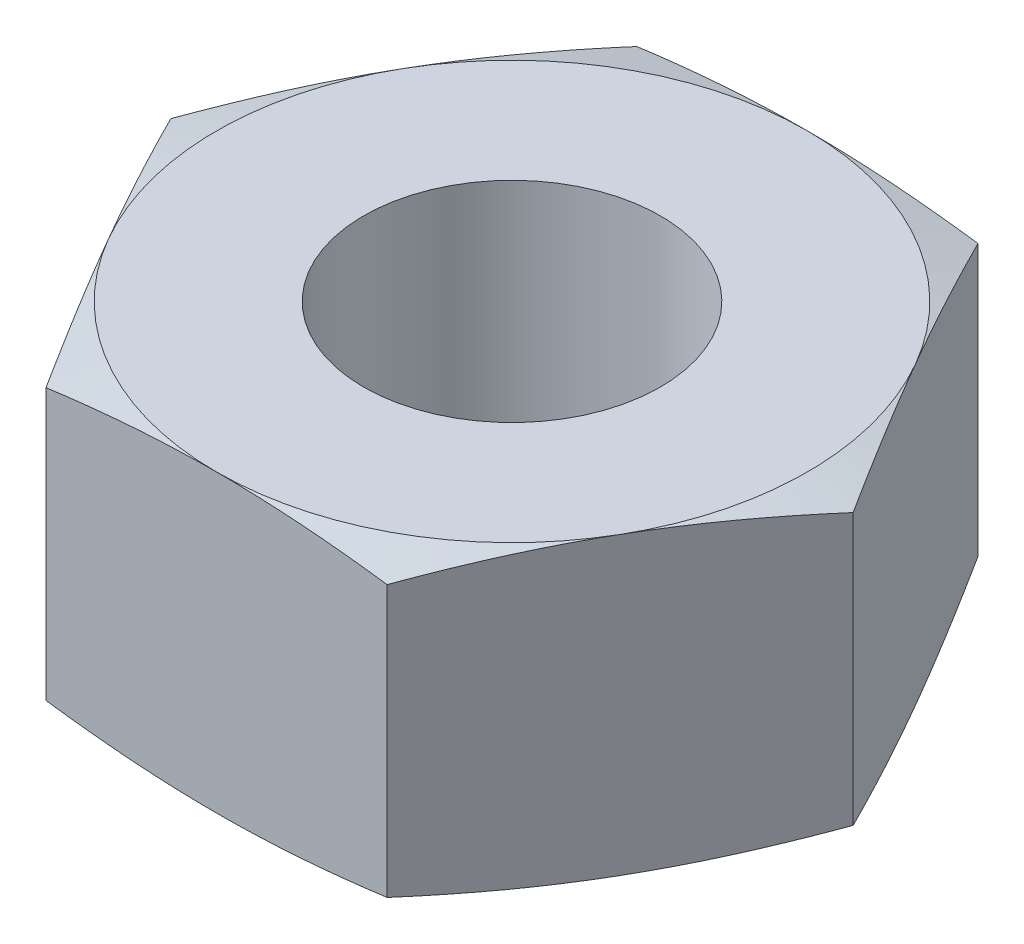
SolidWorks part; units mm, degrees
material "Plain Carbon Steel"
ref_plane "Front Plane" through (0, 0, 0) normal (0, 0, 1) x (1, 0, 0)
ref_plane "Top Plane" through (0, 0, 0) normal (0, 1, 0) x (1, 0, 0)
ref_plane "Right Plane" through (0, 0, 0) normal (1, 0, 0) x (0, 0, -1)
sketch "Sketch1" plane through (0, 0, 0) normal (0, 1, 0) x (1, 0, 0)
  line L1 (4.6188, 0) -> (2.3094, 4)
  line L2 (2.3094, 4) -> (-2.3094, 4)
  line L3 (-2.3094, 4) -> (-4.6188, 0)
  line L4 (-4.6188, 0) -> (-2.3094, -4)
  line L5 (-2.3094, -4) -> (2.3094, -4)
  line L6 (2.3094, -4) -> (4.6188, 0)
  circle A0 centre (0, 0) radius 4 construction
  dimension "D1" = 8
extrude "Extrude1" add sketch "Sketch1" along normal mid plane 4
sketch "Sketch2" plane through (0, 0, 0) normal (1, 0, 0) x (0, 0, -1)
  line L0 (-4, 2) -> (-78.064, -17.8454)
  line L1 (-78.064, -17.8454) -> (-78.064, 2)
  line L2 (-78.064, 2) -> (-4, 2)
  line L3 (0, 0) -> (0, 7.9376) construction
  dimension "D1" = 15
revolve "Cut-Revolve1" cut sketch "Sketch2" angle 360 about L3
mirror "Mirror1" about plane through (0, 0, 0) normal (0, 1, 0) of "Cut-Revolve1"
sketch "Sketch3" plane through (0, 2, 0) normal (0, 1, 0) x (1, 0, 0)
  circle A0 centre (0, 0) radius 2.009
  dimension "D1" = 4.018
extrude "Extrude2" cut sketch "Sketch3" against normal through all
cosmetic thread "Cosmetic Thread1" parameters "D2"=5
